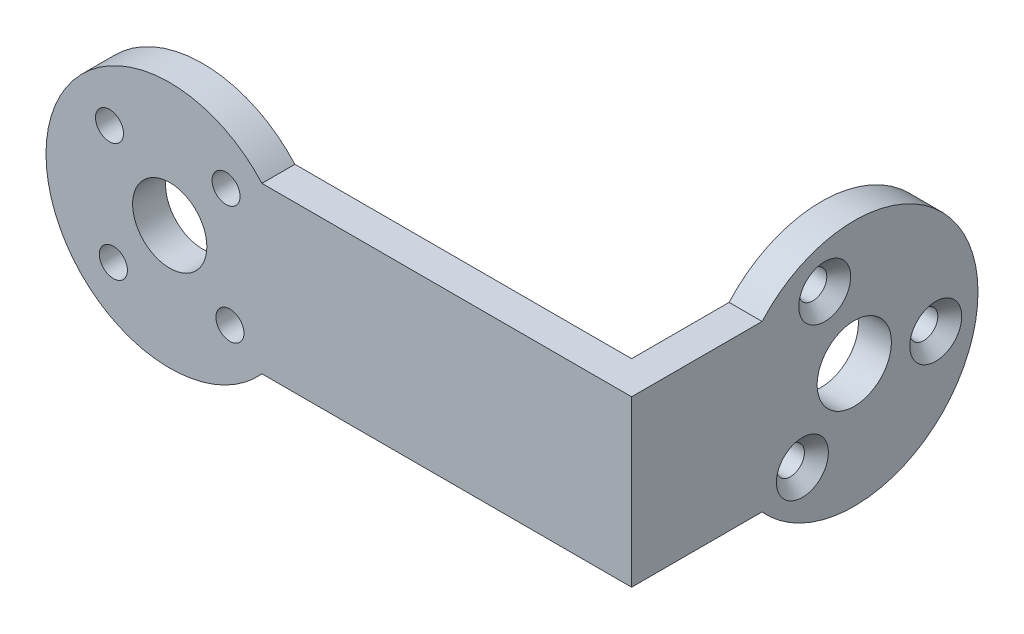
SolidWorks part; units mm, degrees
ref_plane "Plan de face" through (0, 0, 0) normal (0, 0, 1) x (1, 0, 0)
ref_plane "Plan de dessus" through (0, 0, 0) normal (0, 1, 0) x (1, 0, 0)
ref_plane "Plan de droite" through (0, 0, 0) normal (1, 0, 0) x (0, 0, -1)
sketch "Esquisse1" plane through (0, 0, 0) normal (0, 0, 1) x (1, 0, 0)
  line L0 (11.1803, 10) -> (56, 10)
  line L1 (11.1803, -10) -> (56, -10)
  line L2 (56, 10) -> (56, -10)
  arc A0 (11.1803, 10) -> (11.1803, -10) centre (0, 0) ccw
  circle A1 centre (0, 0) radius 4.5
  circle A2 centre (0, 0) radius 10 construction
  circle A3 centre (-7.3034, 6.8308) radius 1.5
  circle A4 centre (6.8308, 7.3034) radius 1.5
  circle A5 centre (7.3034, -6.8308) radius 1.5
  circle A6 centre (-6.8308, -7.3034) radius 1.5
  point P9 (30.5619, 9.4613)
  point P10 (0, 0)
  point P19 (0, 0)
  dimension "D2" = 20
  dimension "D3" = 3
  dimension "D4" = 9
  dimension "D5" = 30
  dimension "D6" = 56
  dimension "D7" = 20
  dimension "D1" = 4
extrude "Boss.-Extru.1" add sketch "Esquisse1" along normal blind 4
sketch "Esquisse3" plane through (56, 0, 0) normal (1, 0, 0) x (0, 0, -1)
  line L0 (0, 10) -> (11.8197, 10)
  line L1 (0, 0) -> (23, 0) construction
  line L2 (0, -10) -> (11.8197, -10)
  line L3 (0, 10) -> (0, -10)
  line L4 (-4, -10) -> (-4, 10) construction
  arc A0 (11.8197, 10) -> (11.8197, -10) centre (23, 0) cw
  circle A1 centre (23, 0) radius 4.5
  circle A2 centre (23, 0) radius 10 construction
  circle A3 centre (19.4163, 9.3358) radius 1.5001
  circle A5 centre (23, 0) radius 10 construction
  circle A7 centre (23, 0) radius 10 construction
  circle A9 centre (23, 0) radius 10 construction
  circle A10 centre (26.5837, -9.3358) radius 1.5001 [skipped]
  circle A11 centre (32.3358, 3.5837) radius 1.5001 [skipped]
  circle A12 centre (13.6642, -3.5837) radius 1.5001 [skipped]
  circle A13 centre (32.8769, -1.5643) radius 1.5001
  circle A14 centre (16.7068, -7.7715) radius 1.5001
  point P12 (40.4613, 0.8545)
  point P13 (0, 0)
  point P15 (23.5237, -7.8391)
  point P22 (23, 0)
  point P24 (23.4392, -7.7715)
  point P25 (23, 0)
  point P26 (0, 0)
  point P35 (-4, 0)
  dimension "D1" = 30
  dimension "D2" = 4
  dimension "D3" = 20
  dimension "D4" = 9
  dimension "D5" = 3
  dimension "D6" = 27
extrude "Boss.-Extru.2" add sketch "Esquisse3" against normal blind 4
hole_wizard "Fraisage pour vis à tête fraisée M31" positions "Esquisse4" profile "Esquisse5" countersink size "M3" standard "Ansi Metric" end condition through all
sketch "Esquisse4" plane through (0, 0, 0) normal (0, 0, -1) x (-1, 0, 0)
  point P0 (-6.8308, 7.3034)
  point P3 (7.3034, 6.8308)
  point P6 (6.8308, -7.3034)
  point P9 (-7.3034, -6.8308)
sketch "Esquisse5" plane through (6.8308, 7.3034, 0) normal (1, 0, 0) x (0, 1, 0)
  line L0 (0, 0) -> (0, 4)
  line L1 (0, 4) -> (1.7, 4)
  line L2 (1.7, 4) -> (1.7, 1.45)
  line L3 (1.7, 1.45) -> (3.15, 0)
  line L5 (3.15, 0) -> (0, 0)
  line L6 (-1.7, 1.45) -> (-3.15, 0) construction
  line L11 (0, -6.35) -> (0, 107.95) construction
  dimension "Diamètre du perçage jusqu'au prochain" = 3.4
  dimension "Profondeur du perçage jusqu'au prochain" = 4
  dimension "Diamètre du fraisage entrant" = 6.3
  dimension "Angle du fraisage entrant" = 90
hole_wizard "Fraisage pour vis à tête fraisée M32" positions "Esquisse6" profile "Esquisse7" countersink size "M3" standard "Ansi Metric" end condition through all
sketch "Esquisse6" plane through (56, 0, 0) normal (1, 0, 0) x (0, 0, -1)
  point P0 (19.4163, 9.3358)
  point P3 (32.8769, -1.5643)
  point P6 (16.7068, -7.7715)
sketch "Esquisse7" plane through (56, 9.3358, -19.4163) normal (0, 1, 0) x (0, 0, -1)
  line L0 (0, 0) -> (0, 71)
  line L1 (0, 71) -> (1.7, 71)
  line L2 (1.7, 71) -> (1.7, 1.45)
  line L3 (1.7, 1.45) -> (3.15, 0)
  line L5 (3.15, 0) -> (0, 0)
  line L6 (-1.7, 1.45) -> (-3.15, 0) construction
  line L11 (0, -6.35) -> (0, 107.95) construction
  dimension "Diamètre du perçage jusqu'au prochain" = 3.4
  dimension "Profondeur du perçage jusqu'au prochain" = 71
  dimension "Diamètre du fraisage entrant" = 6.3
  dimension "Angle du fraisage entrant" = 90
